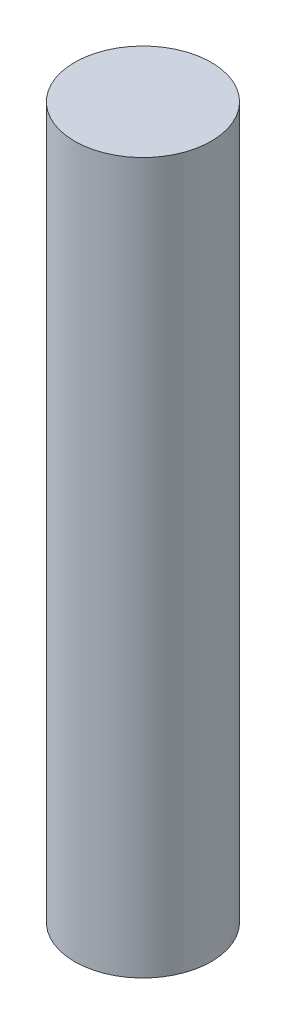
SolidWorks part; units mm, degrees
ref_plane "前视基准面" through (0, 0, 0) normal (0, 0, 1) x (1, 0, 0)
ref_plane "上视基准面" through (0, 0, 0) normal (0, 1, 0) x (1, 0, 0)
ref_plane "右视基准面" through (0, 0, 0) normal (1, 0, 0) x (0, 0, -1)
sketch "草图1" plane through (0, 0, 0) normal (0, 1, 0) x (1, 0, 0)
  circle A0 centre (0, 0) radius 7.5
  dimension "D1" = 15
extrude "凸台-拉伸1" add sketch "草图1" along normal blind 78
